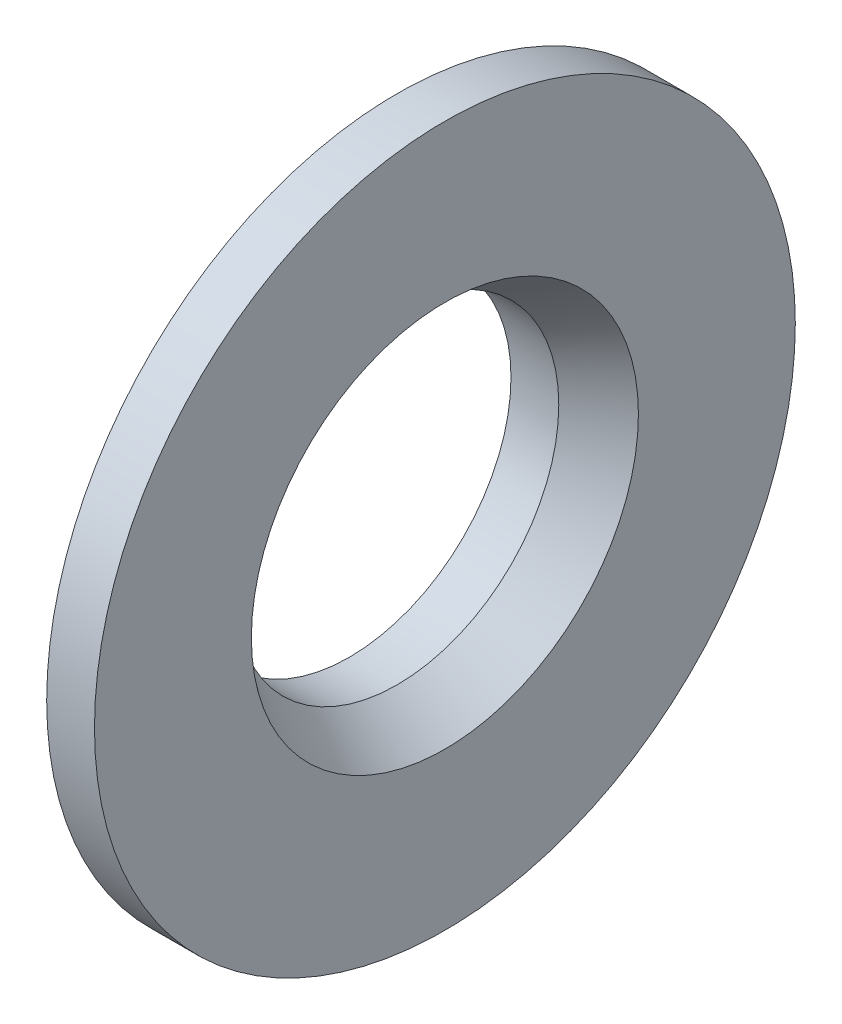
SolidWorks part; units mm, degrees
ref_plane "前视基准面" through (0, 0, 0) normal (0, 0, 1) x (1, 0, 0)
ref_plane "上视基准面" through (0, 0, 0) normal (0, 1, 0) x (1, 0, 0)
ref_plane "右视基准面" through (0, 0, 0) normal (1, 0, 0) x (0, 0, -1)
sketch "草图1" plane through (0, 0, 0) normal (0, 0, 1) x (1, 0, 0)
  line L0 (0, 0) -> (34.9011, 0) construction
  line L2 (6, 12.15) -> (6, 22)
  line L3 (6, 22) -> (3, 22)
  line L4 (3, 22) -> (3, 15)
  line L5 (3, 15) -> (0, 13)
  line L6 (0, 13) -> (0, 10.15)
  line L7 (0, 10.15) -> (3, 10.15)
  line L8 (3, 10.15) -> (6, 12.15)
  dimension "D2" = 13
  dimension "D5" = 3
  dimension "D6" = 3
revolve "旋转1" add sketch "草图1" angle 360 about L0
